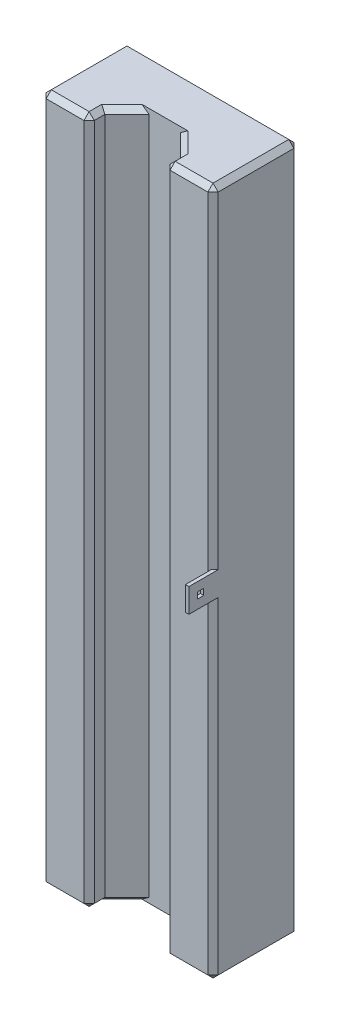
SolidWorks part; units mm, degrees
ref_plane "Front" through (0, 0, 0) normal (0, 0, 1) x (1, 0, 0)
ref_plane "Top" through (0, 0, 0) normal (0, 1, 0) x (1, 0, 0)
ref_plane "Right" through (0, 0, 0) normal (1, 0, 0) x (0, 0, -1)
sketch "Sketch1" plane through (0, 0, 0) normal (0, 0, 1) x (1, 0, 0)
  line L1 (0, 0) -> (50, 0)
  line L2 (0, 0) -> (0, 200)
  line L3 (0, 200) -> (50, 200)
  line L4 (50, 0) -> (50, 200)
  dimension "D1" = 50
  dimension "D2" = 200
extrude "Boss-Extrude1" add sketch "Sketch1" along normal blind 25
sketch "Sketch2" plane through (0, 0, 0) normal (0, -1, 0) x (1, 0, 0)
  line L0 (0, 25) -> (50, 25) construction
  line L1 (29.5563, 36) -> (20.4437, 36)
  line L2 (20.4437, 36) -> (14, 29.5563)
  line L3 (14, 29.5563) -> (14, 20.4437)
  line L4 (14, 20.4437) -> (20.4437, 14)
  line L5 (20.4437, 14) -> (29.5563, 14)
  line L6 (29.5563, 14) -> (36, 20.4437)
  line L7 (36, 20.4437) -> (36, 29.5563)
  line L8 (36, 29.5563) -> (29.5563, 36)
  circle A0 centre (25, 25) radius 11 construction
  dimension "D1" = 22
extrude "Cut-Extrude1" cut sketch "Sketch2" against normal through all
chamfer "Chamfer1" distance 1.5 angle 45 24 edges at (25, 200, 0) (0, 100, 0) (0, 200, 12.5) (32.7782, 200, 17.2218) (36, 200, 22.7218) (7, 200, 25) (17.2218, 200, 17.2218) (14, 200, 22.7218) (50, 200, 12.5) (43, 200, 25) (50, 100, 0) (17.2218, 0, 17.2218) (14, 0, 22.7218) (0, 100, 25) (14, 100, 25) (7, 0, 25) (0, 0, 12.5) (25, 0, 0) (32.7782, 0, 17.2218) (36, 0, 22.7218) (36, 100, 25) (50, 0, 12.5) (43, 0, 25) (50, 100, 25)
sketch "Sketch3" plane through (0, 0, 25) normal (0, 0, 1) x (1, 0, 0)
  line L0 (50, 198.5) -> (50, 1.5) construction
  line L1 (50, 103.5) -> (49, 103.5)
  line L2 (50, 103.5) -> (50, 96.5)
  line L3 (50, 96.5) -> (49, 96.5)
  line L4 (49, 103.5) -> (49, 96.5)
  point P6 (50, 100)
  dimension "D1" = 7
  dimension "D2" = 1
extrude "Boss-Extrude2" add sketch "Sketch3" along normal blind 7 and the other way blind 10
sketch "Sketch4" plane through (50, 0, 0) normal (1, 0, 0) x (0, 0, -1)
  line L0 (-32, 96.5) -> (-32, 103.5) construction
  line L1 (-29.5, 99.1) -> (-27.7, 99.1)
  line L2 (-29.5, 99.1) -> (-29.5, 100.9)
  line L3 (-29.5, 100.9) -> (-27.7, 100.9)
  line L4 (-27.7, 99.1) -> (-27.7, 100.9)
  line L5 (-29.5, 100) -> (-32, 100) construction
  dimension "D1" = 1.8
  dimension "D2" = 2.5
extrude "Cut-Extrude2" cut sketch "Sketch4" against normal blind 7
